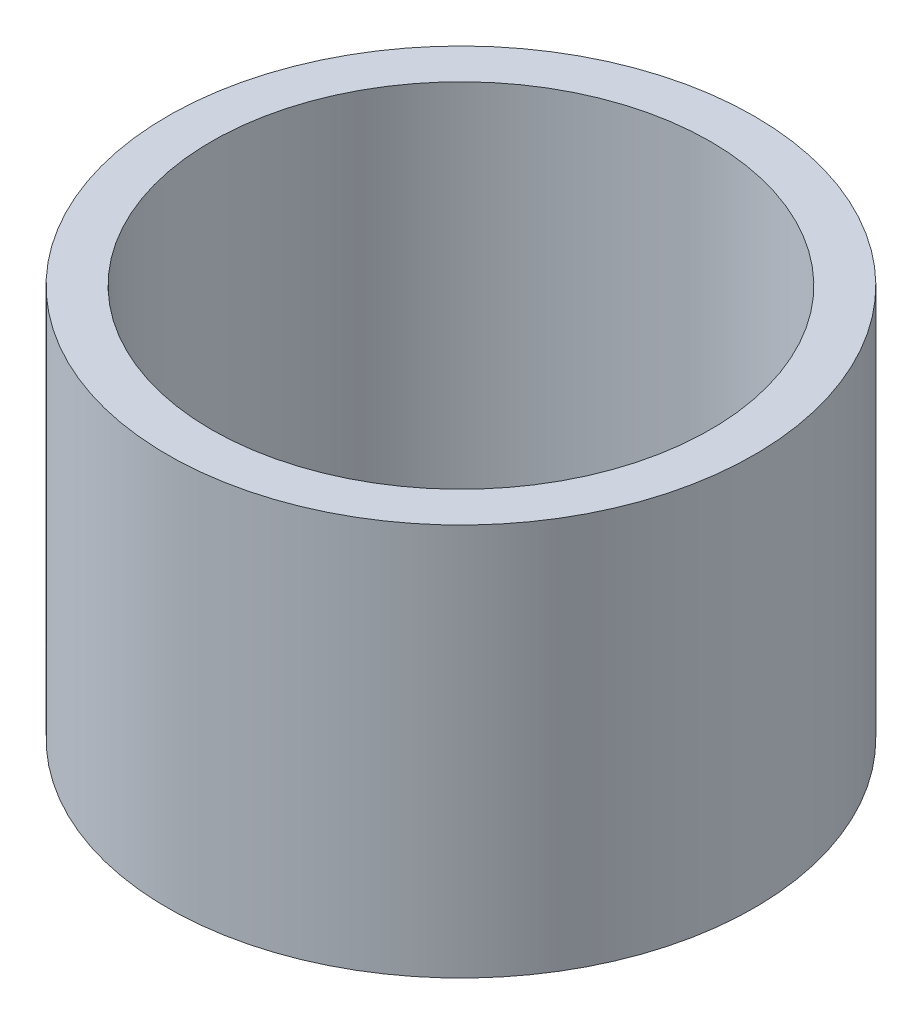
SolidWorks part; units mm, degrees
ref_plane "Plano frontal" through (0, 0, 0) normal (0, 0, 1) x (1, 0, 0)
ref_plane "Plano superior" through (0, 0, 0) normal (0, 1, 0) x (1, 0, 0)
ref_plane "Plano direito" through (0, 0, 0) normal (1, 0, 0) x (0, 0, -1)
sketch "Esboço1" plane through (0, 0, 0) normal (0, 0, 1) x (1, 0, 0)
  line L0 (0, -52.0986) -> (0, 40.1777) construction
  line L2 (17.65, 27.75) -> (20.75, 27.75)
  line L3 (17.65, 27.75) -> (17.65, 0)
  line L4 (17.65, 0) -> (20.75, 0)
  line L5 (20.75, 27.75) -> (20.75, 0)
  line L6 (17.65, 27.75) -> (20.75, 0) construction
  line L7 (17.65, 0) -> (20.75, 27.75) construction
  point P3 (19.2, 13.875)
  dimension "D1" = 17.65
  dimension "D2" = 20.75
  dimension "D3" = 27.75
revolve "Revolução1" add sketch "Esboço1" angle 360 about L0
